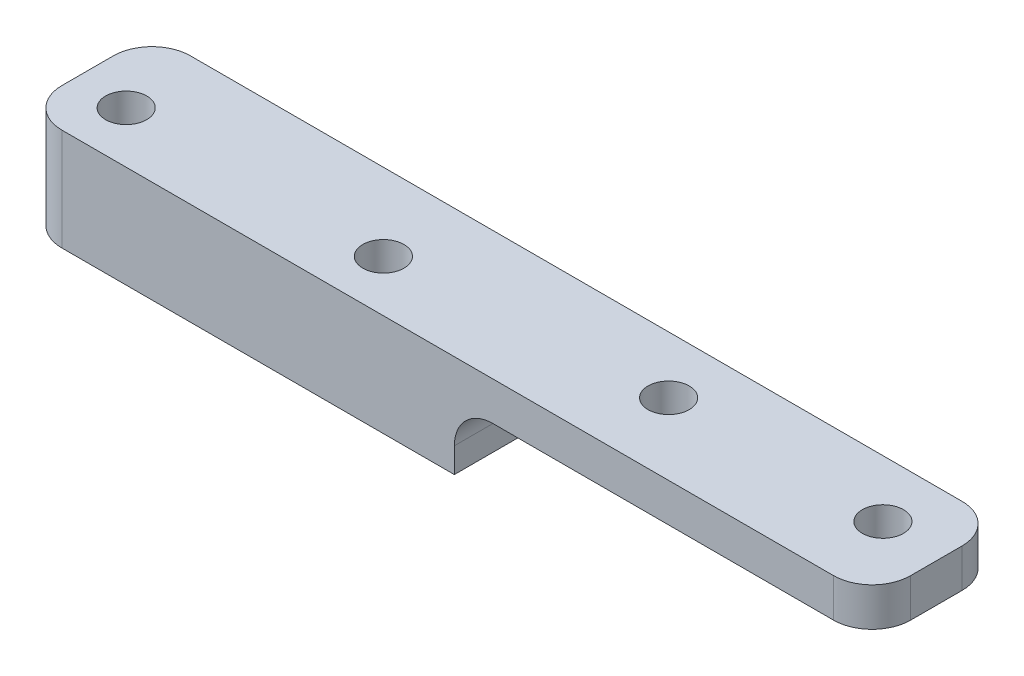
SolidWorks part; units mm, degrees
material "ABS"
ref_plane "Front Plane" through (0, 0, 0) normal (0, 0, 1) x (1, 0, 0)
ref_plane "Top Plane" through (0, 0, 0) normal (0, 1, 0) x (1, 0, 0)
ref_plane "Right Plane" through (0, 0, 0) normal (1, 0, 0) x (0, 0, -1)
other "Configuration Table"
sketch "Sketch1" plane through (0, 0, 0) normal (0, 1, 0) x (1, 0, 0)
  line L0 (0, 0) -> (20, 0) construction
  line L2 (-4, 6) -> (62, 6)
  line L3 (-4, 6) -> (-4, -4)
  line L4 (-4, -4) -> (62, -4)
  line L5 (62, 6) -> (62, -4)
  point P7 (63.2886, 7.0345)
  point P8 (61.7069, 6.6032)
  circle B0 centre (0, 0) radius 1.6
  circle B1 centre (20, 0) radius 1.6
  circle B2 centre (40.6158, 1.5632) radius 1.6
  circle B3 centre (57.278, 1.5632) radius 1.6
  dimension "D1" = 66
  dimension "D2" = 10
  dimension "D3" = 4
  dimension "D4" = 4
sketch_block_instance "Block7-1"
sketch_block "Block7"
extrude "Boss-Extrude1" add sketch "Sketch1" along normal blind 3
sketch "Sketch3" plane through (0, 0, 0) normal (0, -1, 0) x (1, 0, 0)
  line L0 (62, -6) -> (-4, -6) construction
  line L1 (-4, 4) -> (29.5175, 4)
  line L2 (-4, 4) -> (-4, -6)
  line L3 (-4, -6) -> (29.5175, -6)
  line L4 (29.5175, 4) -> (29.5175, -6)
  circle A0 centre (0, 0) radius 1.6 construction
  circle A1 centre (20, 0) radius 1.6 construction
  circle A2 centre (0, 0) radius 1.6
  circle A3 centre (20, 0) radius 1.6
extrude "Boss-Extrude2" add sketch "Sketch3" along normal blind 4.94
fillet "Fillet1" radius 3 5 edges at (29.5175, 0, -1) (-4, -0.97, 4) (-4, -0.97, -6) (62, 1.5, 4) (62, 1.5, -6)
